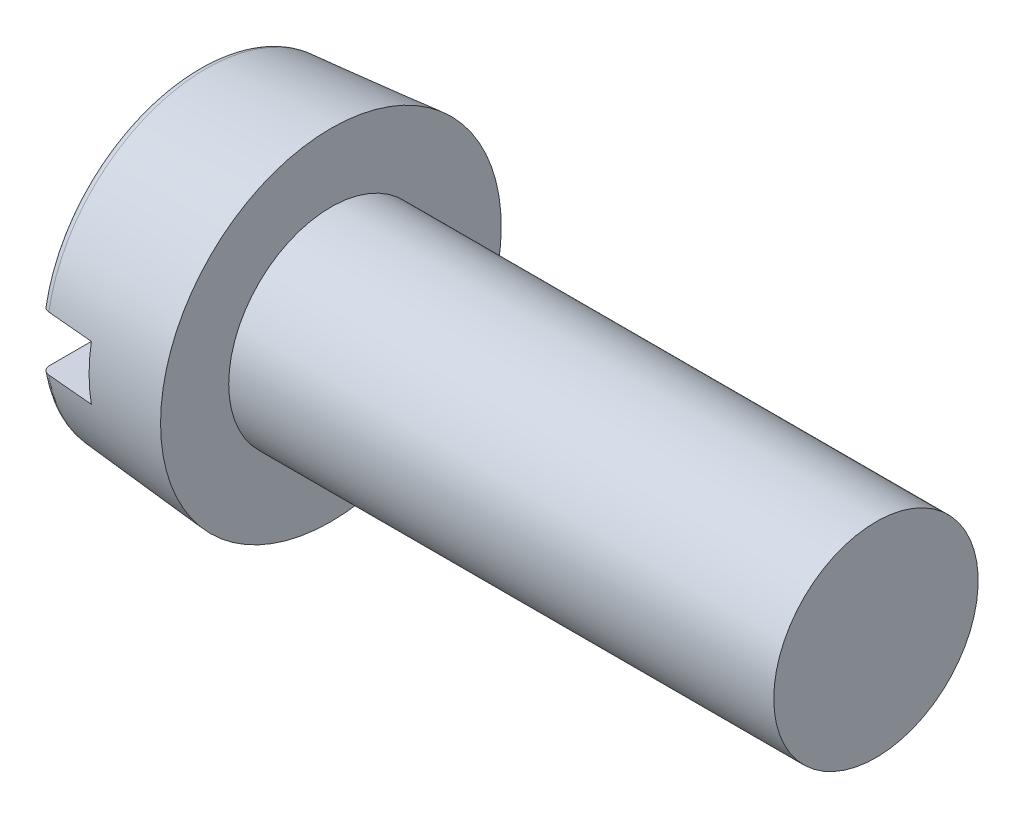
SolidWorks part; units mm, degrees
ref_plane "Plane1" through (0, 0, 0) normal (0, 0, 1) x (1, 0, 0)
ref_plane "Plane2" through (0, 0, 0) normal (0, 1, 0) x (1, 0, 0)
ref_plane "Plane3" through (0, 0, 0) normal (1, 0, 0) x (0, 0, -1)
sketch "BodySke" plane through (0, 0, 0) normal (0, 0, 1) x (1, 0, 0)
  line L0 (3.9, 3) -> (3.9, 5)
  line L1 (0, 0) -> (0, 4.6588)
  line L2 (-25.4, 0) -> (127, 0) construction
  line L3 (19.9, 0) -> (0, 0)
  line L4 (3.9, 3) -> (19.9, 3)
  line L5 (19.9, 3) -> (19.9, 0)
  line L6 (0, 4.6588) -> (3.9, 5)
  line L9 (4.9, 4.5875) -> (4.9, -4.9375) construction
  line L10 (3.9, 6.35) -> (3.9, -3.175) construction
  dimension "Length" = 16
  dimension "Head_ht" = 3.9
  dimension "Advance" = 1
  dimension "Thread_nom" = 16
  dimension "Head_dia" = 10
  dimension "Head_side_angle" = 5
  dimension "Diameter" = 6
revolve "Base-Revolve" add sketch "BodySke"
cosmetic thread "ThreadCosmetic" [suppressed]
fillet "Fillet1" [suppressed] radius 0.25
fillet "Fillet2" radius 0.25 1 edges at (0, 0, 4.6588)
sketch "Sketch2" plane through (0, 0, 0) normal (1, 0, 0) x (0, 0, -1)
  line L0 (5, -0.8) -> (-5, -0.8)
  line L1 (5, -0.8) -> (5, 0.8)
  line L2 (-5, 0.8) -> (5, 0.8)
  line L3 (-5, 0.8) -> (-5, -0.8)
  dimension "D1" = 10
  dimension "Slot_width" = 1.6
  dimension "D2" = 5
  dimension "D3" = 0.8
extrude "Slot" cut sketch "Sketch2" along normal blind 1.6
sketch "ThdSchSke" plane through (0, 0, 0) normal (0, 0, 1) x (1, 0, 0)
  line L0 (5.9, -2.4455) -> (5.5117, -3)
  line L1 (5.9, -2.4455) -> (6.2883, -3)
  line L2 (6.2883, -3) -> (6.2883, -3.75)
  line L3 (-3.175, 0) -> (5.1513, 0) construction
  line L5 (6.2883, -3.75) -> (5.5117, -3.75)
  line L6 (5.5117, -3.75) -> (5.5117, -3)
  dimension "Diameter" = 6
  dimension "SideAngle" = 55
  dimension "VeeAngle" = 70
  dimension "Thread_minor" = 4.891
  dimension "Overcut" = 7.5
  dimension "Start" = 5.9
revolve "ThreadSchematic" [suppressed] cut sketch "ThdSchSke" angle 360 about L3
pattern_linear "ThdSchPat" [suppressed]
equation "\"D1@Sketch2\" = \"Head_dia@BodySke\""
equation "\"D2@Sketch2\" = \"D1@Sketch2\" / 2"
equation "\"D3@Sketch2\" = \"Slot_width@Sketch2\" / 2"
equation "\"Thread_length@ThreadCosmetic\" = ((sgn( (\"Length@BodySke\" - \"Advance@BodySke\" * 2.0 ) - \"Thread_nom@BodySke\" )-1)*( (\"Length@BodySke\" - \"Advance@BodySke\"  * 2.0) - \"Thread_nom@BodySke\" ))/-2+ \"Thread_nom@BodySke\""
equation "\"Thread_minor@ThdSchSke\" = \"Thread_minor@ThreadCosmetic\""
equation "\"Diameter@ThdSchSke\" = \"Diameter@BodySke\""
equation "\"Overcut@ThdSchSke\" = \"Diameter@BodySke\" * 1.25"
equation "\"Start@ThdSchSke\" = \"Head_ht@BodySke\" + \"Length@BodySke\" - \"Thread_length@ThreadCosmetic\"  '---Non-countersunk---"
equation "\"Num_threads@ThdSchPat\" = int( \"Thread_length@ThreadCosmetic\" / \"Advance@BodySke\" + 0.999 )  + 1"
equation "\"Advance@ThdSchPat\" = \"Thread_length@ThreadCosmetic\" /  (\"Num_threads@ThdSchPat\" - 1) 'relax it"
